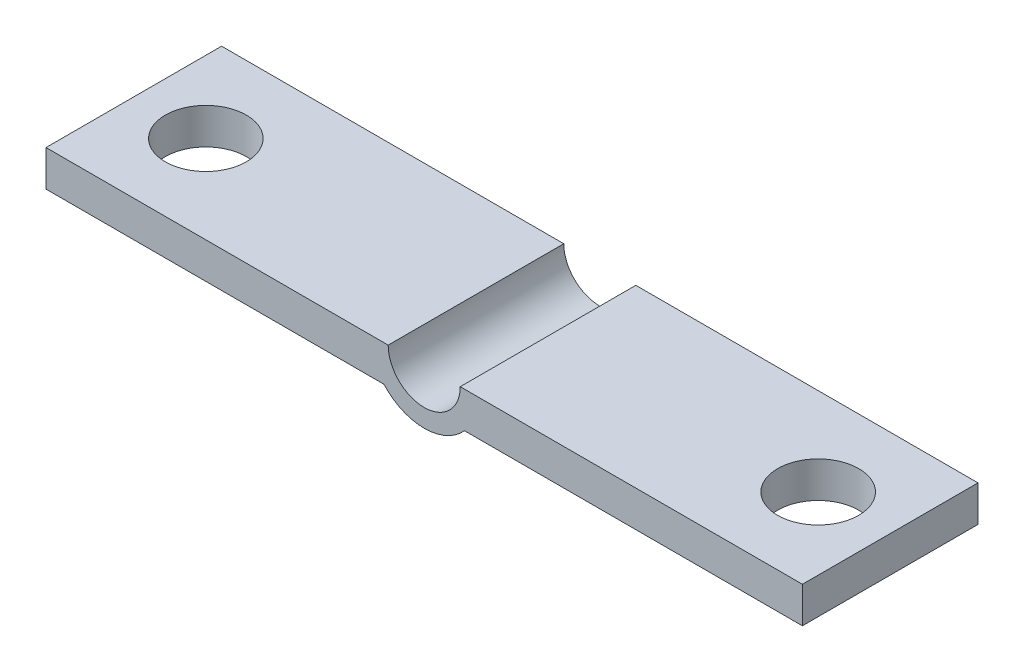
SolidWorks part; units mm, degrees
ref_plane "Front Plane" through (0, 0, 0) normal (0, 0, 1) x (1, 0, 0)
ref_plane "Top Plane" through (0, 0, 0) normal (0, 1, 0) x (1, 0, 0)
ref_plane "Right Plane" through (0, 0, 0) normal (1, 0, 0) x (0, 0, -1)
sketch "Sketch1" plane through (0, 0, 0) normal (0, 0, 1) x (1, 0, 0)
  arc A0 (-2, 0) -> (2, 0) centre (0, 0) ccw
extrude "Extrude-Thin1" add sketch "Sketch1" along normal blind 9.75 thin
sketch "Sketch3" plane through (0, 0, 0) normal (0, 1, 0) x (1, 0, 0)
  line L1 (-21, 0) -> (-2, 0)
  line L2 (-21, 0) -> (-21, -9.75)
  line L3 (-21, -9.75) -> (-2, -9.75)
  line L4 (21, 0) -> (21, -9.75)
  line L5 (2, -9.75) -> (3, -9.75) construction
  line L6 (2, 0) -> (3, 0) construction
  line L7 (-2, 0) -> (-2, -9.75)
  line L8 (2, 0) -> (2, -9.75)
  line L9 (2, 0) -> (21, 0)
  line L10 (2, -9.75) -> (21, -9.75)
  dimension "D1" = 42
extrude "Boss-Extrude1" add sketch "Sketch3" against normal blind 2
sketch "Sketch4" plane through (0, 0, 0) normal (0, 1, 0) x (1, 0, 0)
  line L0 (-21, 0) -> (-21, -9.75) construction
  line L1 (-21, 0) -> (-2, 0) construction
  line L2 (0, -55) -> (0, 55) construction
  circle A0 centre (-17, -4.875) radius 2.25
  circle A1 centre (17, -4.875) radius 2.25
  point P2 (-14.9153, -4.7519)
  point P5 (0, 0)
  point P6 (0, 0)
  dimension "D2" = 4.875
  dimension "D1" = 4
extrude "Cut-Extrude1" cut sketch "Sketch4" against normal through all
